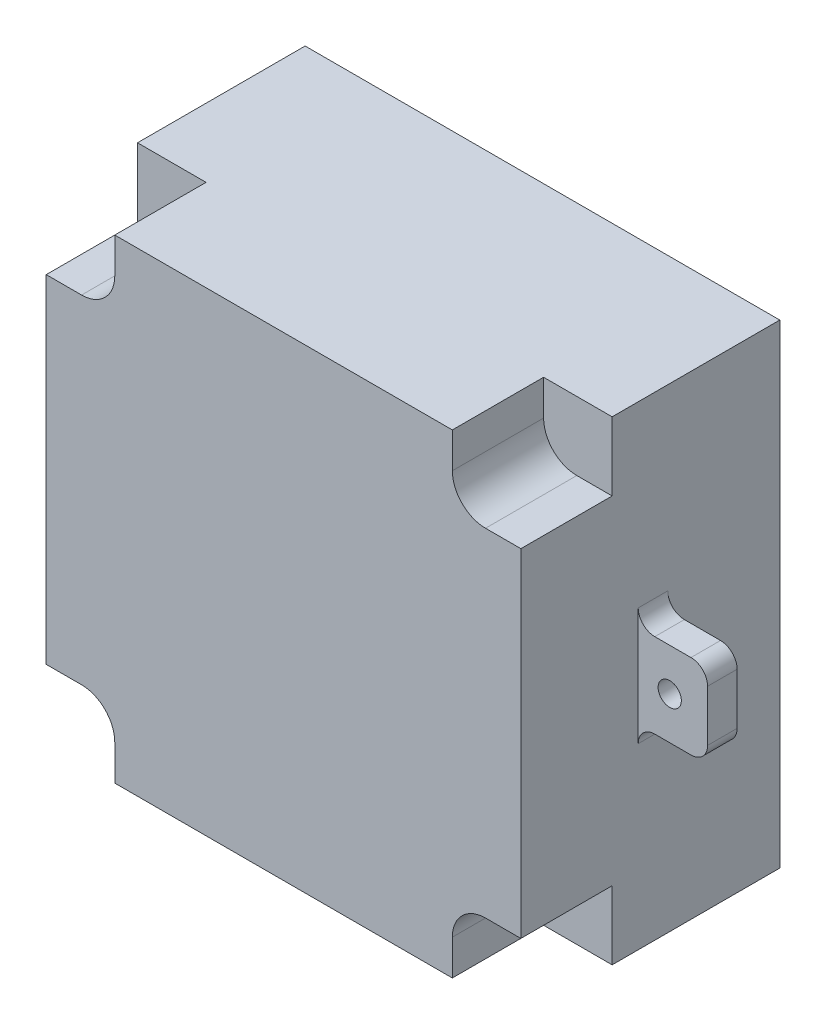
SolidWorks part; units mm, degrees
ref_plane "前视基准面" through (0, 0, 0) normal (0, 0, 1) x (1, 0, 0)
ref_plane "上视基准面" through (0, 0, 0) normal (0, 1, 0) x (1, 0, 0)
ref_plane "右视基准面" through (0, 0, 0) normal (1, 0, 0) x (0, 0, -1)
sketch "草图1" plane through (0, 0, 0) normal (0, 0, 1) x (1, 0, 0)
  line L1 (260.2268, 67.1441) -> (317.4268, 67.1441)
  line L2 (260.2268, 67.1441) -> (260.2268, 9.9441)
  line L3 (260.2268, 9.9441) -> (317.4268, 9.9441)
  line L4 (317.4268, 67.1441) -> (317.4268, 9.9441)
  line L5 (260.2268, 67.1441) -> (317.4268, 9.9441) construction
  line L6 (260.2268, 9.9441) -> (317.4268, 67.1441) construction
  point P0 (288.8268, 38.5441)
  dimension "D1" = 57.2
  dimension "D2" = 57.2
extrude "凸台-拉伸1" add sketch "草图1" along normal blind 20.2
sketch "草图2" plane through (0, 0, 20.2) normal (0, 0, 1) x (1, 0, 0)
  line L0 (317.4268, 67.1441) -> (260.2268, 67.1441) construction
  line L3 (260.2268, 58.8841) -> (268.4868, 58.8841)
  line L4 (268.4868, 67.1441) -> (268.4868, 58.8841)
  line L7 (260.2268, 18.2041) -> (268.4868, 18.2041)
  line L8 (268.4868, 9.9441) -> (268.4868, 18.2041)
  line L10 (309.1668, 67.1441) -> (309.1668, 58.8841)
  line L11 (309.1668, 58.8841) -> (317.4268, 58.8841)
  line L13 (317.4268, 9.9441) -> (317.4268, 67.1441) construction
  line L14 (260.2268, 9.9441) -> (317.4268, 9.9441) construction
  line L15 (317.4268, 18.2041) -> (309.1668, 18.2041)
  line L18 (309.1668, 18.2041) -> (309.1668, 9.9441)
  line L19 (260.2268, 67.1441) -> (260.2268, 9.9441) construction
  line L20 (268.4868, 67.1441) -> (309.1668, 67.1441)
  line L21 (317.4268, 58.8841) -> (317.4268, 18.2041)
  line L22 (309.1668, 9.9441) -> (268.4868, 9.9441)
  line L23 (260.2268, 18.2041) -> (260.2268, 58.8841)
  dimension "D1" = 8.26
extrude "凸台-拉伸2" add sketch "草图2" along normal blind 11
fillet "圆角1" radius 4 4 edges at (268.4868, 18.2041, 25.7) (309.1668, 18.2041, 25.7) (309.1668, 58.8841, 25.7) (268.4868, 58.8841, 25.7)
ref_plane "基准面4" through (0, 0, 13.5) normal (0, 0, -1) x (-1, 0, 0)
sketch "草图3" plane through (0, 0, 13.5) normal (0, 0, -1) x (-1, 0, 0)
  line L0 (-317.4268, 9.9441) -> (-317.4268, 67.1441) construction
  line L1 (-260.2268, 43.6291) -> (-251.8668, 43.6291)
  line L2 (-260.2268, 43.6291) -> (-260.2268, 33.4591)
  line L3 (-260.2268, 33.4591) -> (-251.8668, 33.4591)
  line L4 (-251.8668, 43.6291) -> (-251.8668, 33.4591)
  line L5 (-260.2268, 43.6291) -> (-251.8668, 33.4591) construction
  line L6 (-260.2268, 33.4591) -> (-251.8668, 43.6291) construction
  line L7 (-325.7868, 43.6291) -> (-317.4268, 43.6291)
  line L8 (-325.7868, 43.6291) -> (-325.7868, 33.4591)
  line L9 (-325.7868, 33.4591) -> (-317.4268, 33.4591)
  line L10 (-317.4268, 43.6291) -> (-317.4268, 33.4591)
  line L11 (-325.7868, 43.6291) -> (-317.4268, 33.4591) construction
  line L12 (-325.7868, 33.4591) -> (-317.4268, 43.6291) construction
  line L13 (-260.2268, 67.1441) -> (-260.2268, 9.9441) construction
  point P0 (-256.0468, 38.5441)
  point P5 (-321.6068, 38.5441)
  point P12 (-317.4268, 38.5441)
  point P13 (0, 0)
  point P14 (0, 0)
  dimension "D1" = 8.36
  dimension "D2" = 10.17
extrude "凸台-拉伸3" add sketch "草图3" against normal blind 3.56
fillet "圆角2" radius 2 8 edges at (317.4268, 33.4591, 15.28) (325.7868, 33.4591, 15.28) (317.4268, 43.6291, 15.28) (325.7868, 43.6291, 15.28) (260.2268, 33.4591, 15.28) (251.8668, 33.4591, 15.28) (251.8668, 43.6291, 15.28) (260.2268, 43.6291, 15.28)
sketch "草图4" plane through (0, 0, 13.5) normal (0, 0, -1) x (-1, 0, 0)
  line L0 (-317.4268, 9.9441) -> (-317.4268, 67.1441) construction
  line L1 (-260.2268, 67.1441) -> (-260.2268, 9.9441) construction
  circle A0 centre (-256.4268, 38.5441) radius 1.4
  circle A1 centre (-321.2268, 38.5441) radius 1.4
  point P6 (-317.4268, 38.5441)
  dimension "D1" = 2.8
  dimension "D2" = 3.8
  dimension "D3" = 3.8
extrude "切除-拉伸1" cut sketch "草图4" against normal up to next
